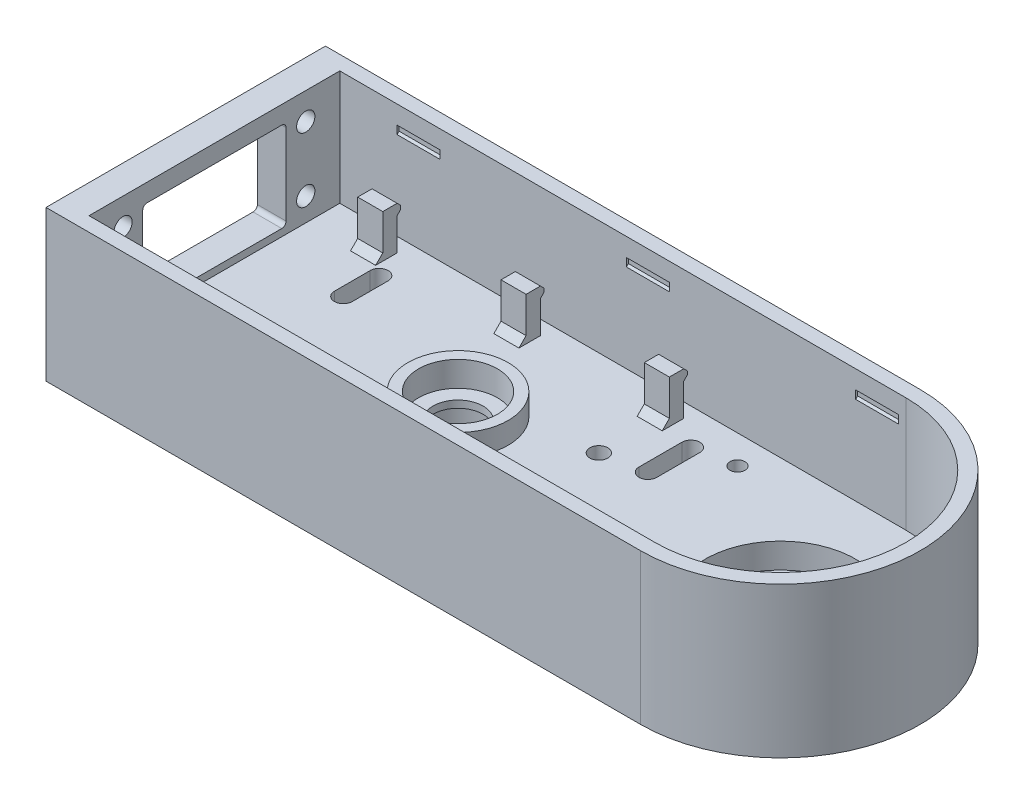
SolidWorks part; units mm, degrees
ref_plane "Front Plane" through (0, 0, 0) normal (0, 0, 1) x (1, 0, 0)
ref_plane "Top Plane" through (0, 0, 0) normal (0, 1, 0) x (1, 0, 0)
ref_plane "Right Plane" through (0, 0, 0) normal (1, 0, 0) x (0, 0, -1)
sketch "Sketch1" plane through (0, 0, 0) normal (0, 1, 0) x (1, 0, 0)
  line L0 (0, 39) -> (-166, 39)
  line L1 (-166, 39) -> (-166, -39)
  line L2 (-166, -39) -> (0, -39)
  arc A0 (0, -39) -> (0, 39) centre (0, 0) ccw
  dimension "D1" = 78
  dimension "D2" = 166
extrude "Boss-Extrude1" add sketch "Sketch1" along normal blind 10
sketch "Sketch2" plane through (0, 10, 0) normal (0, 1, 0) x (1, 0, 0)
  line L0 (0, 35) -> (-158, 35)
  line L2 (-158, -35) -> (0, -35)
  line L3 (0, 39) -> (-166, 39)
  line L4 (-166, 39) -> (-166, -39)
  line L5 (-166, -39) -> (0, -39)
  line L6 (0, 39) -> (-166, 39)
  line L7 (-166, 39) -> (-166, -39)
  line L8 (-166, -39) -> (0, -39)
  line L9 (-158, 35) -> (-158, -35)
  line L10 (0, 35) -> (-162, 35) construction
  line L11 (-162, -35) -> (0, -35) construction
  line L13 (-162, 35) -> (-162, -35) construction
  arc A0 (0, -35) -> (0, 35) centre (0, 0) ccw
  arc A1 (0, -39) -> (0, 39) centre (0, 0) ccw
  arc A2 (0, -39) -> (0, 39) centre (0, 0) ccw
  dimension "D3" = 8
  dimension "D1" = 0
  dimension "D2" = 4
extrude "Boss-Extrude2" add sketch "Sketch2" along normal blind 32 contours L0 L9 L2 A0
sketch "Sketch3" plane through (-166, 0, 0) normal (-1, 0, 0) x (0, 0, 1)
  line L0 (-39, 0) -> (39, 0) construction
  line L1 (-20, 12) -> (20, 12)
  line L2 (-20, 12) -> (-20, 37)
  line L3 (-20, 37) -> (20, 37)
  line L4 (20, 12) -> (20, 37)
  line L5 (-20, 12) -> (20, 37) construction
  line L6 (-20, 37) -> (20, 12) construction
  circle A0 centre (-25.5, 34.5) radius 2.55
  circle A1 centre (-25.5, 16.5) radius 2.55
  circle A2 centre (25.5, 16.5) radius 2.55
  circle A3 centre (25.5, 34.5) radius 2.55
  point P0 (0, 24.5)
  dimension "D5" = 5.1
  dimension "D6" = 5.1
  dimension "D7" = 5.1
  dimension "D8" = 5.1
  dimension "D1" = 25
  dimension "D2" = 40
  dimension "D3" = 12
  dimension "D4" = 16.5
  dimension "D9" = 5.5
  dimension "D10" = 5.5
  dimension "D11" = 18
extrude "Cut-Extrude1" cut sketch "Sketch3" against normal up to next
fillet "Fillet1" radius 1.2 4 edges at (-162, 37, 20) (-162, 12, 20) (-162, 37, -20) (-162, 12, -20)
sketch "Sketch4" plane through (0, 10, 0) normal (0, 1, 0) x (1, 0, 0)
  line L0 (-91.7844, 7.0785) -> (-7.1622, 28.4111) construction
  line L1 (-91.7844, -7.0785) -> (-7.1622, -28.4111) construction
  line L2 (-90, 0) -> (0, 0) construction
  line L3 (-90, 0) -> (-238, 0) construction
  line L4 (-238.8216, 6.2966) -> (-93.2995, 25.2856) construction
  line L5 (-238.8216, -6.2966) -> (-93.2995, -25.2856) construction
  arc A0 (-7.1622, -28.4111) -> (-7.1622, 28.4111) centre (0, 0) ccw construction
  arc A1 (-91.7844, 7.0785) -> (-91.7844, -7.0785) centre (-90, 0) ccw construction
  circle A2 centre (-90, 0) radius 7
  circle A3 centre (0, 0) radius 17.5
  arc A4 (-238.8216, 6.2966) -> (-238.8216, -6.2966) centre (-238, 0) ccw construction
  arc A5 (-93.2995, -25.2856) -> (-93.2995, 25.2856) centre (-90, 0) ccw construction
  dimension "D1" = 58.6
  dimension "D2" = 14.6
  dimension "D4" = 35
  dimension "D5" = 14
  dimension "D7" = 51
  dimension "D8" = 12.7
  dimension "D3" = 90
  dimension "D6" = 148
extrude "Cut-Extrude2" cut sketch "Sketch4" against normal through all
sketch "Sketch5" plane through (0, 10, 0) normal (0, 1, 0) x (1, 0, 0)
  circle A0 centre (0, 0) radius 21
  dimension "D1" = 42
extrude "Cut-Extrude3" cut sketch "Sketch5" against normal blind 7
sketch "Sketch6" plane through (0, 10, 0) normal (0, 1, 0) x (1, 0, 0)
  circle A0 centre (-90, 0) radius 11
  circle A1 centre (-90, 0) radius 14
  dimension "D1" = 22
  dimension "D2" = 3
extrude "Boss-Extrude3" add sketch "Sketch6" along normal blind 6
sketch "Sketch7" plane through (0, 10, 0) normal (0, 1, 0) x (1, 0, 0)
  line L0 (-135, 23) -> (-135, 13) construction
  line L1 (-132.5, 23) -> (-132.5, 13)
  line L2 (-137.5, 23) -> (-137.5, 13)
  line L3 (-135, -13) -> (-135, -23) construction
  line L4 (-132.5, -13) -> (-132.5, -23)
  line L5 (-137.5, -13) -> (-137.5, -23)
  line L6 (-158, 35) -> (-158, -35) construction
  line L7 (0, 35) -> (-158, 35) construction
  line L8 (-158, -35) -> (0, -35) construction
  line L9 (-50, 25) -> (-50, 13) construction
  line L10 (-47.5, 25) -> (-47.5, 13)
  line L11 (-52.5, 25) -> (-52.5, 13)
  line L12 (0, 35) -> (-158, 35) construction
  line L13 (-50, -21) -> (-50, -25) construction
  line L14 (-47.5, -21) -> (-47.5, -25)
  line L15 (-52.5, -21) -> (-52.5, -25)
  arc A0 (-132.5, 23) -> (-137.5, 23) centre (-135, 23) ccw
  arc A1 (-137.5, 13) -> (-132.5, 13) centre (-135, 13) ccw
  arc A2 (-132.5, -13) -> (-137.5, -13) centre (-135, -13) ccw
  arc A3 (-137.5, -23) -> (-132.5, -23) centre (-135, -23) ccw
  arc A4 (-47.5, 25) -> (-52.5, 25) centre (-50, 25) ccw
  arc A5 (-52.5, 13) -> (-47.5, 13) centre (-50, 13) ccw
  arc A6 (-47.5, -21) -> (-52.5, -21) centre (-50, -21) ccw
  arc A7 (-52.5, -25) -> (-47.5, -25) centre (-50, -25) ccw
  point P2 (-135, 18)
  point P7 (-135, -18)
  point P22 (-50, 19)
  point P31 (-50, -23)
  dimension "D1" = 2.5
  dimension "D2" = 2.5
  dimension "D9" = 2.5
  dimension "D12" = 2.5
  dimension "D3" = 23
  dimension "D4" = 10
  dimension "D5" = 12
  dimension "D6" = 12
  dimension "D7" = 10
  dimension "D8" = 108
  dimension "D10" = 10
  dimension "D11" = 12
  dimension "D13" = 4
  dimension "D14" = 10
extrude "Cut-Extrude4" cut sketch "Sketch7" against normal through all
sketch "Sketch8" plane through (0, 0, 0) normal (0, -1, 0) x (1, 0, 0)
  circle A0 centre (-90, 0) radius 11
  dimension "D1" = 22
extrude "Cut-Extrude5" cut sketch "Sketch8" against normal blind 7
sketch "Sketch9" plane through (0, 10, 0) normal (0, 1, 0) x (1, 0, 0)
  line L0 (0, 35) -> (-158, 35) construction
  line L1 (-158, 35) -> (-158, -35) construction
  line L2 (-158, -35) -> (0, -35) construction
  line L3 (-58, -9.46) -> (-49.612, -5) construction
  line L4 (-158, -35) -> (0, -35) construction
  circle A0 centre (-39, 27) radius 2.1
  arc A1 (-47.5, 25) -> (-52.5, 25) centre (-50, 25) ccw construction
  circle A2 centre (-61.5, 10.8097) radius 2.5
  arc A3 (-52.5, 13) -> (-47.5, 13) centre (-50, 13) ccw construction
  circle A4 centre (-58, -9.46) radius 1.6
  circle A5 centre (-49.612, -5) radius 1.6
  dimension "D1" = 8
  dimension "D2" = 11
  dimension "D3" = 4.2
  dimension "D6" = 5
  dimension "D9" = 3.2
  dimension "D10" = 3.2
  dimension "D4" = 24.1903
  dimension "D5" = 11.5
  dimension "D7" = 100
  dimension "D8" = 9.5
  dimension "D11" = 30
  dimension "D12" = 28
extrude "Cut-Extrude6" cut sketch "Sketch9" against normal through all
ref_plane "Plane1" through (-145, 0, 0) normal (1, 0, 0) x (0, 0, -1)
sketch "Sketch10" plane through (-145, 0, 0) normal (1, 0, 0) x (0, 0, -1)
  line L0 (31, 10) -> (31, 19)
  line L1 (35, 10) -> (-35, 10) construction
  line L2 (31, 19) -> (32, 20)
  line L3 (32, 20) -> (32, 21)
  line L4 (32, 21) -> (31, 22)
  line L5 (31, 22) -> (27, 22)
  line L6 (27, 22) -> (27, 10)
  line L8 (35, 10) -> (-35, 10)
  line L9 (35, 42) -> (35, 10) construction
  dimension "D1" = 4
  dimension "D2" = 4
  dimension "D3" = 3
  dimension "D4" = 4
  dimension "D5" = 135
  dimension "D6" = 135
  dimension "D7" = 1
  dimension "D8" = 12
extrude "Boss-Extrude4" add sketch "Sketch10" along normal blind 7 contours L8 L0 L2 L3 L4 L5 L6
chamfer "Chamfer1" distance 2 angle 45 1 edges at (-141.5, 10, -27)
pattern_linear "LPattern1" count 3 spacing 40 along (1, 0, 0) of "Boss-Extrude4", "Chamfer1"
ref_plane "Plane2" through (-142, 0, 0) normal (-1, 0, 0) x (0, 0, 1)
sketch "Sketch11" plane through (-142, 0, 0) normal (-1, 0, 0) x (0, 0, 1)
  line L7 (-35, 42) -> (-35, 10) construction
  line L8 (-35, 42) -> (-35, 10)
  line L19 (-35, 42) -> (35, 42) construction
  line L20 (-35, 42) -> (35, 42)
  line L21 (-34.4, 42) -> (-34.4, 37.5)
  line L22 (-34.4, 37.5) -> (-35.55, 36.35)
  line L23 (-35.55, 36.35) -> (-35.55, 35.15)
  line L24 (-35.55, 35.15) -> (-34.4, 34)
  line L25 (-34.4, 34) -> (-30.9, 34)
  line L26 (-30.9, 34) -> (-30.9, 42)
  line L27 (-39, 42) -> (-39, 0) construction
  dimension "D7" = 3.5
  dimension "D8" = 3.5
  dimension "D9" = 1.2
  dimension "D10" = 135
  dimension "D11" = 135
  dimension "D12" = 8
  dimension "D13" = 4.5
  dimension "D14" = 4.6
extrude "Cut-Extrude7" cut sketch "Sketch11" against normal blind 12 contours L23 L24 L8 L22
pattern_linear "LPattern2" count 3 spacing 64 along (1, 0, 0) of "Cut-Extrude7"
mirror "Mirror1" about plane through (0, 0, 0) normal (0, 0, 1) of "LPattern2", "Cut-Extrude7"
sketch "Sketch12" plane through (0, 0, 0) normal (0, 0, 1) x (1, 0, 0)
  line L0 (39, 42) -> (0, 42) construction
  line L1 (39, 42) -> (0, 42)
  line L2 (34.4, 42) -> (34.4, 37.5)
  line L3 (34.4, 37.5) -> (35.55, 36.35)
  line L4 (35.55, 36.35) -> (35.55, 35.15)
  line L5 (35.55, 35.15) -> (34.4, 34)
  line L6 (34.4, 34) -> (30.9, 34)
  line L7 (30.9, 34) -> (30.9, 42)
  line L8 (35, 42) -> (35, 32.2725)
  line L9 (0, 42) -> (0, 38.3259)
  dimension "D1" = 3.5
  dimension "D2" = 3.5
  dimension "D3" = 8
  dimension "D4" = 135
  dimension "D5" = 1.2
  dimension "D6" = 4.5
  dimension "D7" = 4.6
  dimension "D8" = 4
revolve "Cut-Revolve1" cut sketch "Sketch12" angle 20 mid plane about L9
sketch "Sketch13" plane through (0, 10, 0) normal (0, 1, 0) x (1, 0, 0)
  circle A1 centre (-90, 0) radius 11
  circle A2 centre (-90, 0) radius 11
  dimension "D1" = 0
extrude "Cut-Extrude8" cut sketch "Sketch13" against normal blind 1
